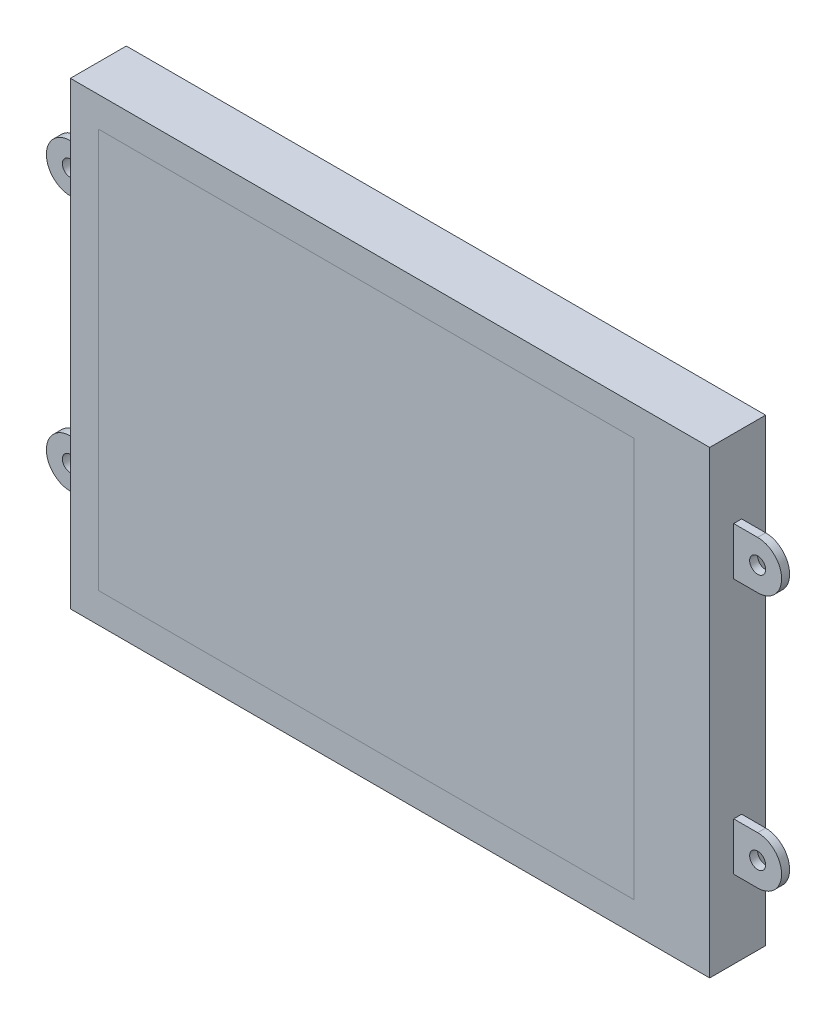
SolidWorks part; units mm, degrees
ref_plane "Front Plane" through (0, 0, 0) normal (0, 0, 1) x (1, 0, 0)
ref_plane "Top Plane" through (0, 0, 0) normal (0, 1, 0) x (1, 0, 0)
ref_plane "Right Plane" through (0, 0, 0) normal (1, 0, 0) x (0, 0, -1)
sketch "Sketch1" plane through (0, 0, 0) normal (0, 0, 1) x (1, 0, 0)
  line L1 (-40, -28.75) -> (40, -28.75)
  line L2 (-40, -28.75) -> (-40, 28.75)
  line L3 (-40, 28.75) -> (40, 28.75)
  line L4 (40, -28.75) -> (40, 28.75)
  line L5 (-40, -28.75) -> (40, 28.75) construction
  line L6 (-40, 28.75) -> (40, -28.75) construction
  point P0 (0, 0)
  dimension "D1" = 57.5
  dimension "D2" = 80
extrude "Boss-Extrude1" add sketch "Sketch1" along normal mid plane 7
sketch "Sketch3" plane through (0, 0, 0) normal (0, 0, 1) x (1, 0, 0)
  line L0 (40, 19) -> (43, 19)
  line L1 (-43, -16) -> (43, -16) construction
  line L2 (-43, -16) -> (-43, 16) construction
  line L3 (-43, 16) -> (43, 16) construction
  line L4 (43, -16) -> (43, 16) construction
  line L5 (-43, -16) -> (43, 16) construction
  line L6 (-43, 16) -> (43, -16) construction
  line L7 (40, -28.75) -> (40, 28.75) construction
  line L8 (43, 13) -> (40, 13)
  line L9 (43, -19) -> (40, -19)
  line L10 (43, -13) -> (40, -13)
  line L11 (-43, 19) -> (-40, 19)
  line L12 (-40, 28.75) -> (-40, -28.75) construction
  line L13 (-43, 13) -> (-40, 13)
  line L14 (-40, 13) -> (-40, 19)
  line L15 (-43, -13) -> (-40, -13)
  line L16 (-40, -13) -> (-40, -19)
  line L17 (-40, -19) -> (-43, -19)
  line L18 (40, 19) -> (40, 13)
  line L19 (40, -13) -> (40, -19)
  arc A0 (43, 13) -> (43, 19) centre (43, 16) ccw
  arc A1 (43, -19) -> (43, -13) centre (43, -16) ccw
  arc A2 (-43, 19) -> (-43, 13) centre (-43, 16) ccw
  arc A3 (-43, -13) -> (-43, -19) centre (-43, -16) ccw
  circle A4 centre (-43, -16) radius 1
  circle A5 centre (-43, 16) radius 1
  circle A6 centre (43, 16) radius 1
  circle A7 centre (43, -16) radius 1
  point P0 (0, 0)
  dimension "D1" = 2
  dimension "D2" = 6
  dimension "D3" = 32
  dimension "D4" = 86
extrude "Boss-Extrude2" add sketch "Sketch3" along normal mid plane 1
sketch "Sketch5" plane through (0, 0, 3.5) normal (0, 0, 1) x (1, 0, 0)
  line L0 (-40, 28.75) -> (-40, -28.75) construction
  line L1 (-36.5, 25) -> (30.5, 25)
  line L2 (-36.5, 25) -> (-36.5, -25)
  line L3 (-36.5, -25) -> (30.5, -25)
  line L4 (30.5, 25) -> (30.5, -25)
  line L5 (-36.5, 25) -> (30.5, -25) construction
  line L6 (-36.5, -25) -> (30.5, 25) construction
  point P0 (-3, 0)
  point P5 (-9.5755, 0)
  point P6 (-10.4467, 0)
  point P8 (-3.8043, 0)
  dimension "D1" = 50
  dimension "D2" = 67
  dimension "D3" = 3.5
split line "Split Line1"
